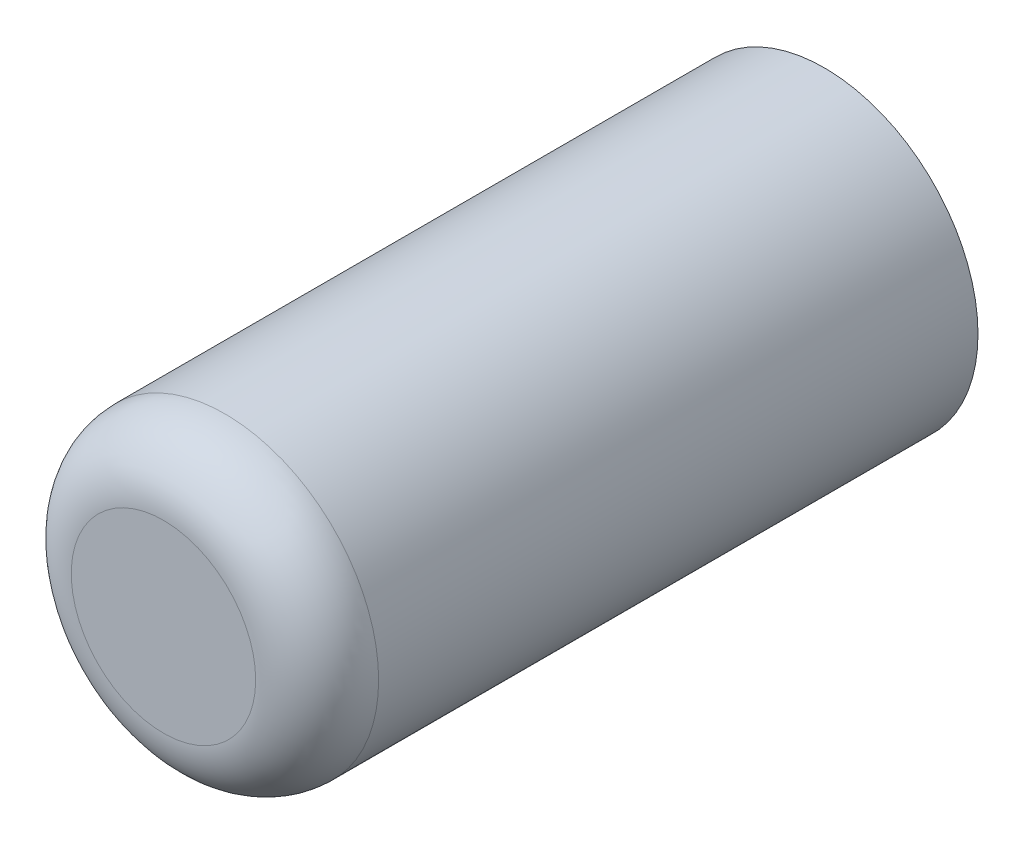
SolidWorks part; units mm, degrees
ref_plane "Front Plane" through (0, 0, 0) normal (0, 0, 1) x (1, 0, 0)
ref_plane "Top Plane" through (0, 0, 0) normal (0, 1, 0) x (1, 0, 0)
ref_plane "Right Plane" through (0, 0, 0) normal (1, 0, 0) x (0, 0, -1)
sketch "Sketch1" plane through (0, 0, 0) normal (0, 0, 1) x (1, 0, 0)
  line L0 (0, 0) -> (0, 2.25)
  line L1 (0, 2.25) -> (2.681, 2.25)
  line L2 (2.681, 2.25) -> (-2.681, 2.25)
  arc A0 (-2.681, 2.25) -> (2.681, 2.25) centre (0, 0) ccw
  circle A1 centre (0, 0) radius 5
  dimension "D1" = 7
  dimension "D3" = 10
  dimension "D2" = 2.25
extrude "Boss-Extrude1" add sketch "Sketch1" along normal blind 11.5 contours A1 A0 L2 L1
sketch "Sketch2" plane through (0, 0, 11.5) normal (0, 0, 1) x (1, 0, 0)
  circle A0 centre (0, 0) radius 5
  dimension "D1" = 10
extrude "Boss-Extrude2" add sketch "Sketch2" along normal blind 10
fillet "Fillet2" radius 2 1 edges at (5, 0, 21.5)
